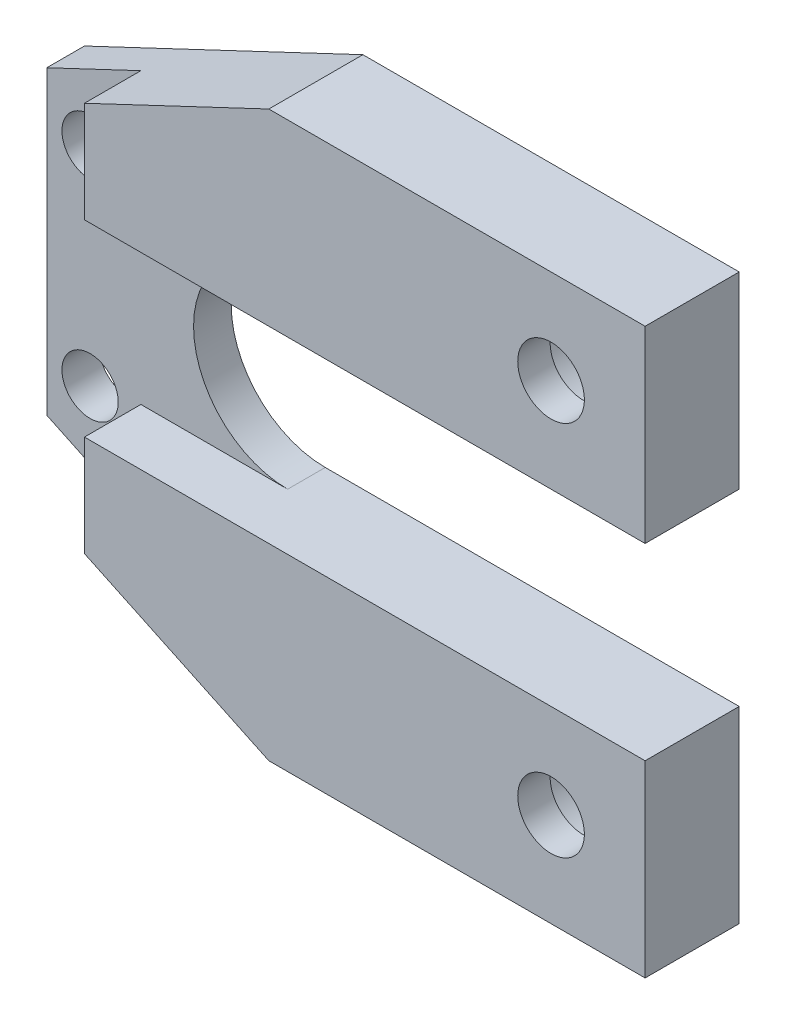
SolidWorks part; units mm, degrees
ref_plane "Front Plane" through (0, 0, 0) normal (0, 0, 1) x (1, 0, 0)
ref_plane "Top Plane" through (0, 0, 0) normal (0, 1, 0) x (1, 0, 0)
ref_plane "Right Plane" through (0, 0, 0) normal (1, 0, 0) x (0, 0, -1)
sketch "Sketch1" plane through (0, 0, 0) normal (0, 1, 0) x (1, 0, 0)
  line L1 (0, 0) -> (6.35, 0)
  line L2 (0, 0) -> (0, 2.54)
  line L3 (0, 2.54) -> (44.196, 2.54)
  line L4 (44.196, -0.8146) -> (44.196, 2.54)
  line L6 (6.35, 0) -> (6.35, -3.81)
  line L7 (6.35, -3.81) -> (44.196, -3.81)
  line L8 (44.196, -0.8146) -> (44.196, -3.81)
  dimension "D1" = 37.846
  dimension "D2" = 2.54
  dimension "D3" = 3.81
  dimension "D4" = 6.35
extrude "Boss-Extrude1" add sketch "Sketch1" along normal blind 38.1
hole_wizard "CBORE for #8 Socket Head Cap Screw1" positions "3DSketch1" profile "Sketch2" counterbore size "#8" standard "ANSI Inch" end condition through all
sketch3d "3DSketch1"
  line L1 (44.196, 38.1, -2.54) -> (44.196, 0, -2.54) construction
  line L2 (44.196, 0, -2.54) -> (0, 0, -2.54) construction
  point P0 (37.846, 31.75, -2.54)
  point P2 (37.846, 6.35, -2.54)
  dimension "D1" = 6.35
  dimension "D2" = 25.4
  dimension "D3" = 6.35
sketch "Sketch2" plane through (37.846, 31.75, -2.54) normal (1, 0, 0) x (0, 1, 0)
  line L0 (0, 0) -> (0, 6.35)
  line L1 (0, 6.35) -> (2.2479, 6.35)
  line L3 (2.2479, 6.35) -> (2.2479, 4.1656)
  line L4 (2.2479, 4.1656) -> (3.9687, 4.1656)
  line L5 (3.9687, 4.1656) -> (3.9687, 0)
  line L7 (3.9687, 0) -> (0, 0)
  line L11 (0, -6.35) -> (0, 107.95) construction
  dimension "Thru Hole Dia." = 4.4958
  dimension "Thru Hole Depth" = 6.35
  dimension "C'Bore Dia." = 7.9375
  dimension "C'Bore Depth" = 4.1656
sketch "Sketch3" plane through (0, 0, -2.54) normal (0, 0, -1) x (-1, 0, 0)
  line L0 (0, 29.21) -> (-18.796, 38.1)
  line L1 (0, 38.1) -> (0, 0) construction
  line L2 (-44.196, 38.1) -> (0, 38.1) construction
  line L3 (0, 8.89) -> (-18.796, 0)
  line L4 (-44.196, 0) -> (0, 0) construction
  line L5 (-44.196, 38.1) -> (-44.196, 0) construction
  line L6 (-18.796, 38.1) -> (0, 38.1)
  line L7 (0, 38.1) -> (0, 29.21)
  line L8 (0, 8.89) -> (0, 0)
  line L9 (0, 0) -> (-18.796, 0)
  dimension "D1" = 25.4
  dimension "D2" = 20.32
  dimension "D3" = 8.89
extrude "Cut-Extrude1" cut sketch "Sketch3" against normal through all
hole_wizard "#6 Clearance Hole1" positions "3DSketch2" profile "Sketch4" hole size "#6" standard "ANSI Inch" end condition through all
sketch3d "3DSketch2"
  line L0 (0, 29.21, -2.54) -> (0, 8.89, -2.54) construction
  line L2 (0, 8.89, -2.54) -> (5.6359, 8.89, -2.54) construction
  point P0 (2.921, 26.035, -2.54)
  point P2 (2.921, 12.065, -2.54)
  dimension "D1" = 2.921
  dimension "D2" = 13.97
  dimension "D3" = 3.175
sketch "Sketch4" plane through (2.921, 26.035, -2.54) normal (1, 0, 0) x (0, 1, 0)
  line L0 (0, 0) -> (0, 6.35)
  line L1 (0, 6.35) -> (1.8986, 6.35)
  line L2 (1.8986, 6.35) -> (1.8986, 0)
  line L5 (1.8986, 0) -> (0, 0)
  line L11 (0, -6.35) -> (0, 107.95) construction
  dimension "Thru Hole Dia." = 3.7973
  dimension "Thru Hole Depth" = 6.35
sketch "Sketch5" plane through (0, 0, -2.54) normal (0, 0, -1) x (-1, 0, 0)
  line L0 (-16.256, 12.7) -> (-44.196, 12.7)
  line L1 (-44.196, 38.1) -> (-44.196, 0) construction
  line L2 (-16.256, 25.4) -> (-44.196, 25.4)
  line L3 (-44.196, 12.7) -> (-44.196, 25.4)
  line L4 (-44.196, 38.1) -> (-18.796, 38.1) construction
  arc A0 (-16.256, 12.7) -> (-16.256, 25.4) centre (-16.256, 19.05) ccw
  dimension "D1" = 12.7
  dimension "D2" = 27.94
  dimension "D3" = 12.7
extrude "Cut-Extrude2" cut sketch "Sketch5" against normal through all
sketch "Sketch6" plane through (0, 0, 3.81) normal (0, 0, 1) x (1, 0, 0)
  line L0 (6.35, 32.2134) -> (6.35, 5.8866) construction
  line L1 (16.256, 25.4) -> (6.35, 25.4)
  line L2 (16.256, 25.4) -> (16.256, 12.7)
  line L3 (16.256, 12.7) -> (6.35, 12.7)
  line L4 (6.35, 25.4) -> (6.35, 12.7)
  line L5 (44.196, 12.7) -> (16.256, 12.7) construction
extrude "Cut-Extrude3" cut sketch "Sketch6" against normal up to surface (3.81 mm away) up to face at (1.0224, 26.035, 0)
equation "\"D3@Sketch3\"=0.35"
